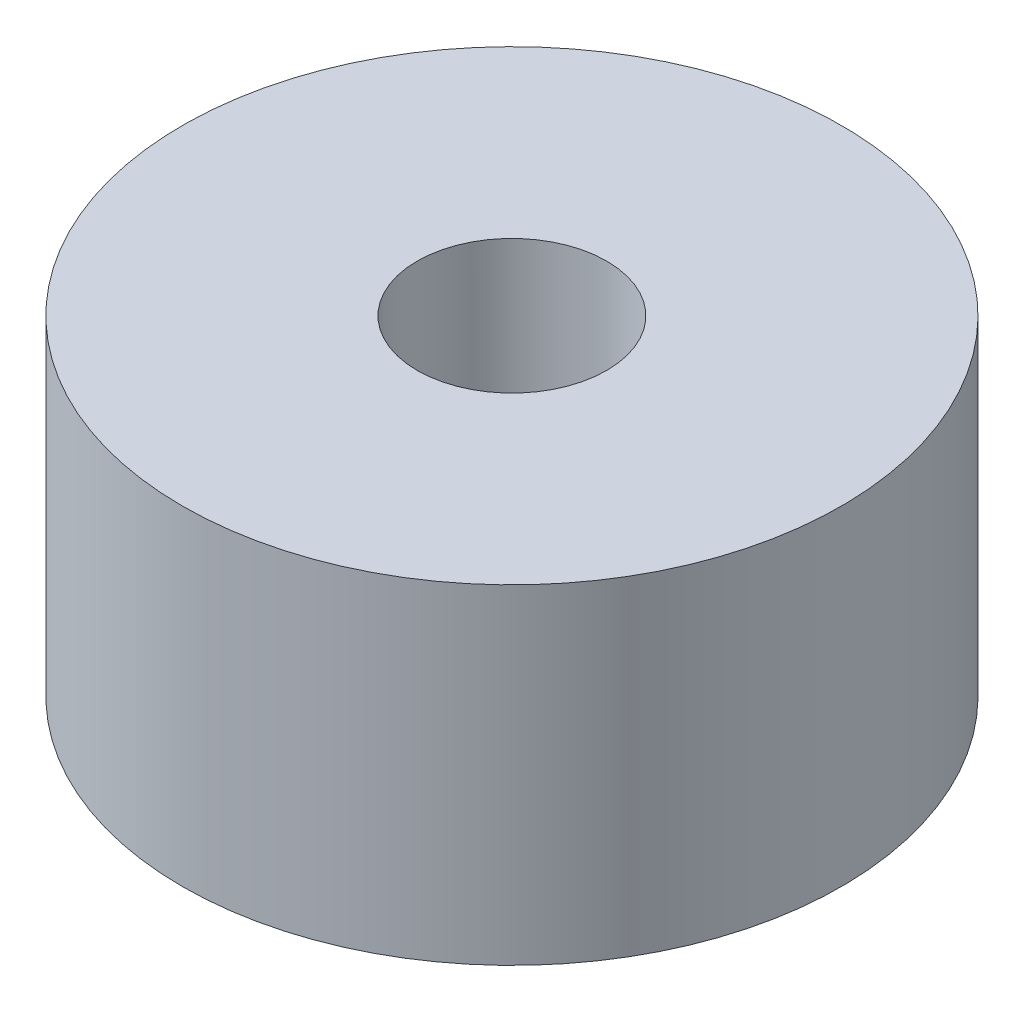
SolidWorks part; units mm, degrees
ref_plane "Front Plane" through (0, 0, 0) normal (0, 0, 1) x (1, 0, 0)
ref_plane "Top Plane" through (0, 0, 0) normal (0, 1, 0) x (1, 0, 0)
ref_plane "Right Plane" through (0, 0, 0) normal (1, 0, 0) x (0, 0, -1)
sketch "Sketch2" plane through (0, 0, 0) normal (0, 1, 0) x (1, 0, 0)
  line L1 (-8.6, -5.5) -> (8.6, -5.5)
  line L2 (-8.6, -5.5) -> (-8.6, 5.5)
  line L3 (-8.6, 5.5) -> (8.6, 5.5)
  line L4 (8.6, -5.5) -> (8.6, 5.5)
  line L5 (-8.6, -5.5) -> (8.6, 5.5) construction
  line L6 (-8.6, 5.5) -> (8.6, -5.5) construction
  point P0 (0, 0)
  dimension "D1" = 17.2
  dimension "D2" = 11
sketch "Sketch3" plane through (0, 0, 0) normal (0, 1, 0) x (1, 0, 0)
  circle A0 centre (0, 0) radius 12
extrude "Boss-Extrude1" add sketch "Sketch3" along normal blind 12
extrude "Cut-Extrude1" cut sketch "Sketch2" along normal blind 2.2
sketch "Sketch4" plane through (0, 0, 0) normal (0, 1, 0) x (1, 0, 0)
  circle A0 centre (0, 0) radius 3.45
extrude "Cut-Extrude2" cut sketch "Sketch4" along normal through all
sketch "Sketch5" plane through (0, 2.2, 0) normal (0, -1, 0) x (1, 0, 0)
  line L0 (-8.6, -5.5) -> (-8.6, 5.5) construction
  line L1 (-8.6, 1.25) -> (-6.9013, 1.25)
  line L2 (-8.6, 1.25) -> (-8.6, -1.25)
  line L3 (-8.6, -1.25) -> (-6.9013, -1.25)
  line L4 (-6.9013, 1.25) -> (-6.9013, -1.25)
  dimension "D1" = 2.5
  dimension "D2" = 1.25
extrude "Cut-Extrude3" cut sketch "Sketch5" against normal blind 2.5
fillet "Fillet1" radius 0.5 3 edges at (-7.7507, 2.2, -1.25) (-7.7507, 2.2, 1.25) (-6.9013, 2.2, 0)
